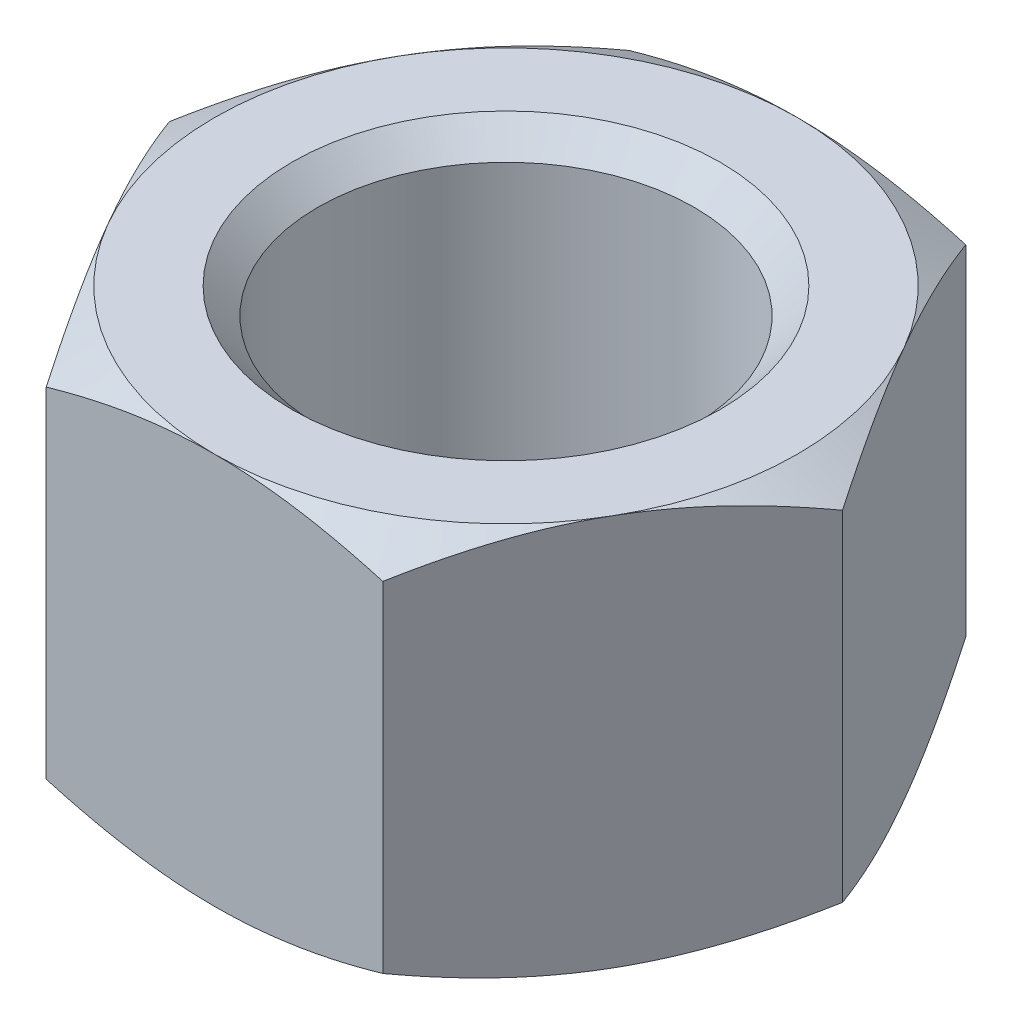
SolidWorks part; units mm, degrees
material "一般碳鋼"
ref_plane "前基準面" through (0, 0, 0) normal (0, 0, 1) x (1, 0, 0)
ref_plane "上基準面" through (0, 0, 0) normal (0, 1, 0) x (1, 0, 0)
ref_plane "右基準面" through (0, 0, 0) normal (1, 0, 0) x (0, 0, -1)
sketch "Sketch1" plane through (0, 0, 0) normal (0, 1, 0) x (1, 0, 0)
  line L1 (5.5, 9.5263) -> (-5.5, 9.5263)
  line L2 (-5.5, 9.5263) -> (-11, 0)
  line L3 (-11, 0) -> (-5.5, -9.5263)
  line L4 (-5.5, -9.5263) -> (5.5, -9.5263)
  line L5 (5.5, -9.5263) -> (11, 0)
  line L6 (11, 0) -> (5.5, 9.5263)
  circle A0 centre (0, 0) radius 11 construction
  circle A1 centre (0, 0) radius 9.5263 construction
  dimension "D1" = 22
extrude "Extrude1" add sketch "Sketch1" along normal blind 12.8
hole_wizard "d" positions "Sketch3" profile "Sketch2" tap size "M3" standard "ISO" end condition through all
sketch "Sketch3" plane through (0, 12.8, 0) normal (0, 1, 0) x (-1, 0, 0)
  point P0 (0, 0)
sketch "Sketch2" plane through (0, 12.8, 0) normal (1, 0, 0) x (0, 0, 1)
  line L0 (0, 0) -> (0, 12.8)
  line L1 (0, 12.8) -> (6.15, 12.8)
  line L2 (6.15, 12.8) -> (6.15, 0)
  line L5 (6.15, 0) -> (0, 0)
  line L11 (0, -6.35) -> (0, 107.95) construction
  dimension "Thru Tap Drill Dia." = 12.3
  dimension "Thru Tap Drill Depth" = 12.8
cosmetic thread "Hole Thread2" parameters "D2"=14
sketch "Sketch5" plane through (0, 0, 0) normal (1, 0, 0) x (0, 0, -1)
  line L0 (-9.5263, 12.8) -> (-11.5, 11.6605)
  line L1 (-11.5, 11.6605) -> (-11.5, 12.8)
  line L2 (-11.5, 12.8) -> (-9.5263, 12.8)
  line L3 (0, 0) -> (0, 5.0612) construction
  line L4 (-9.5263, 6.4) -> (-1.064, 6.4) construction
  line L5 (-9.5263, 12.8) -> (-9.5263, 0) construction
  line L6 (-11.5, 0) -> (-9.5263, 0)
  line L7 (-11.5, 1.1395) -> (-11.5, 0)
  line L8 (-9.5263, 0) -> (-11.5, 1.1395)
  dimension "D1" = 30
  dimension "D2" = 23
revolve "Cut-Revolve1" cut sketch "Sketch5" angle 360 about L3
sketch "Sketch7" plane through (0, 0, 0) normal (1, 0, 0) x (0, 0, -1)
  line L0 (0, 0) -> (0, 3.9238) construction
  line L1 (-7, 12.8) -> (-6.15, 12.8)
  line L2 (-6.15, 12.8) -> (-6.15, 11.95)
  line L3 (-6.15, 11.95) -> (-7, 12.8)
  line L4 (4.7631, 12.8) -> (-4.7631, 12.8) construction
  line L6 (-6.15, 12.8) -> (-6.15, 0) construction
  line L7 (-9.5263, 6.4) -> (-0.5606, 6.4) construction
  line L8 (-9.5263, 11.9491) -> (-9.5263, 0.8509) construction
  line L9 (-6.15, 0.85) -> (-7, 0)
  line L10 (-6.15, 0) -> (-6.15, 0.85)
  line L11 (-7, 0) -> (-6.15, 0)
  dimension "D2" = 14
revolve "Cut-Revolve2" cut sketch "Sketch7" angle 360 about L0
equation "\"D2@Sketch7\" = \"D2@Hole Thread2\""
equation "\"D2@Sketch5\" = \"D1@Sketch1\"+1"
